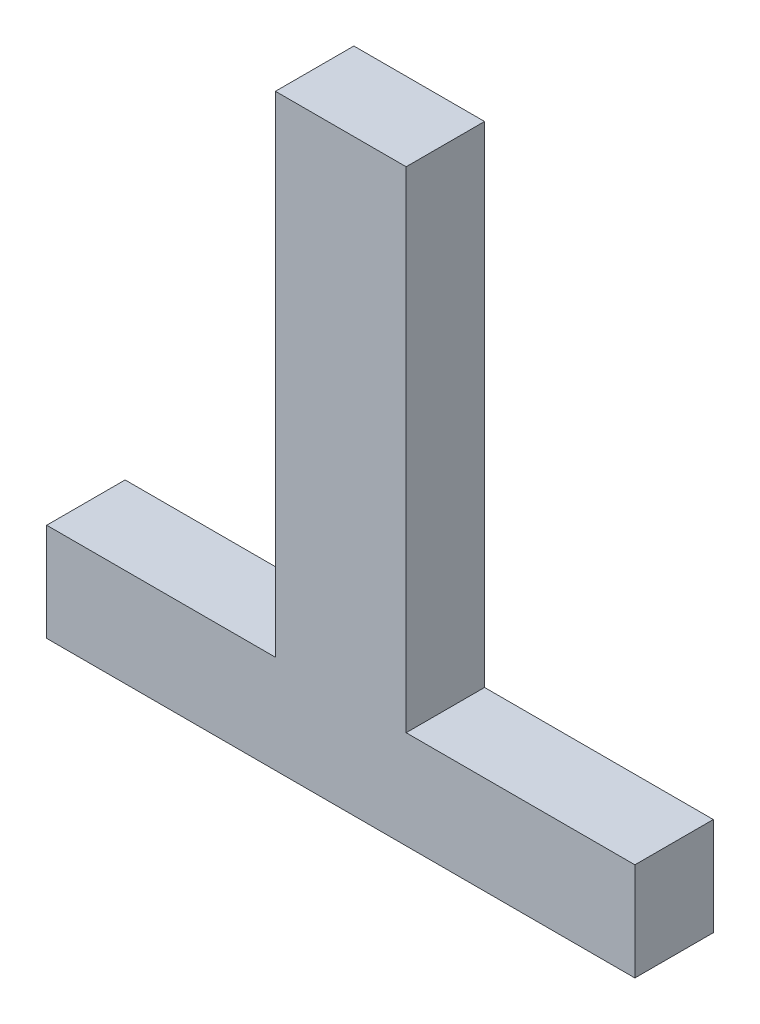
SolidWorks part; units mm, degrees
ref_plane "前视基准面" through (0, 0, 0) normal (0, 0, 1) x (1, 0, 0)
ref_plane "上视基准面" through (0, 0, 0) normal (0, 1, 0) x (1, 0, 0)
ref_plane "右视基准面" through (0, 0, 0) normal (1, 0, 0) x (0, 0, -1)
other "Configuration Table"
sketch "草图1" plane through (0, 0, 0) normal (0, 0, 1) x (1, 0, 0)
  line L0 (-45, 0) -> (45, 0)
  line L1 (45, 0) -> (45, 15)
  line L2 (45, 15) -> (10, 15)
  line L3 (10, 15) -> (10, 90)
  line L4 (10, 90) -> (-10, 90)
  line L5 (-10, 90) -> (-10, 15)
  line L6 (-10, 15) -> (-45, 15)
  line L7 (-45, 15) -> (-45, 0)
extrude "凸台-拉伸1" add sketch "草图1" along normal blind 12
